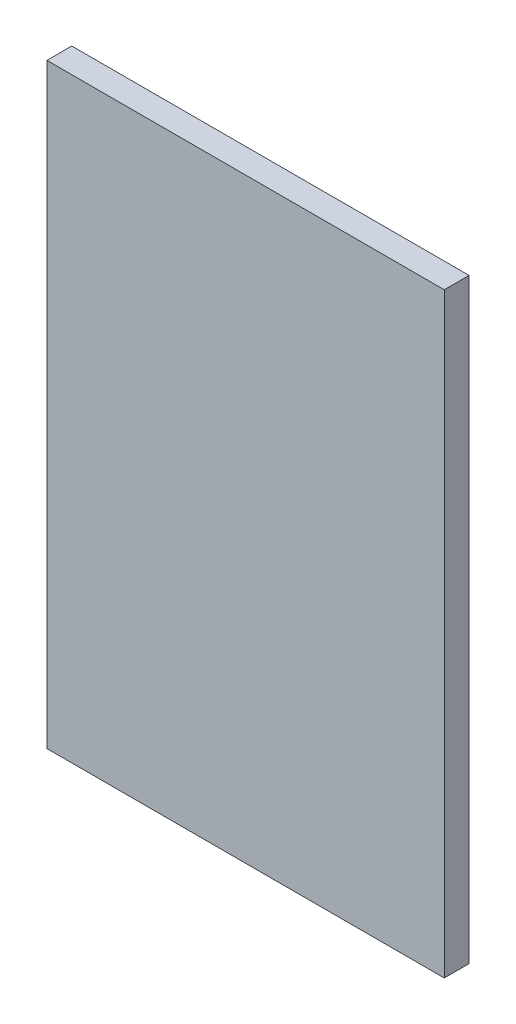
SolidWorks part; units mm, degrees
material "6061 Alloy"
ref_plane "Front Plane" through (0, 0, 0) normal (0, 0, 1) x (1, 0, 0)
ref_plane "Top Plane" through (0, 0, 0) normal (0, 1, 0) x (1, 0, 0)
ref_plane "Right Plane" through (0, 0, 0) normal (1, 0, 0) x (0, 0, -1)
sketch "Sketch1" plane through (0, 0, 0) normal (0, 0, 1) x (1, 0, 0)
  line L1 (0, 0) -> (50.8, 0)
  line L2 (0, 0) -> (0, -76.2)
  line L3 (0, -76.2) -> (50.8, -76.2)
  line L4 (50.8, 0) -> (50.8, -76.2)
extrude "Boss-Extrude1" add sketch "Sketch1" along normal blind 3.175
